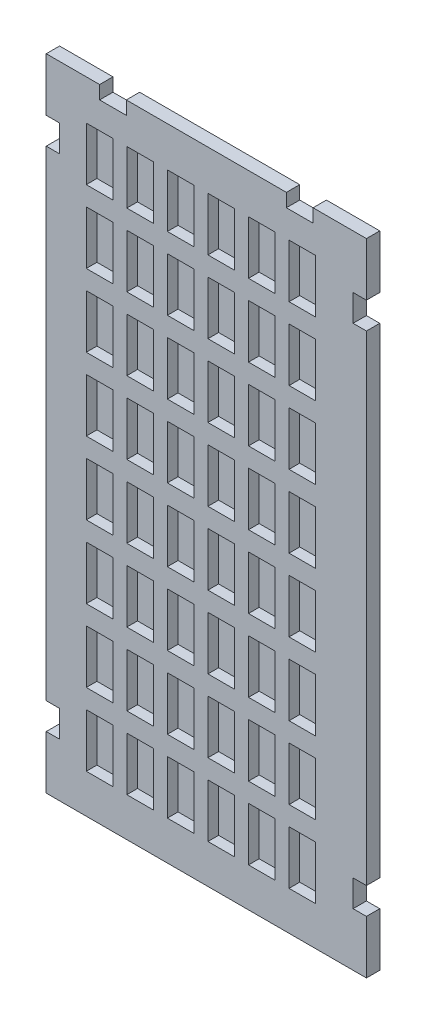
SolidWorks part; units mm, degrees
ref_plane "Front Plane" through (0, 0, 0) normal (0, 0, 1) x (1, 0, 0)
ref_plane "Top Plane" through (0, 0, 0) normal (0, 1, 0) x (1, 0, 0)
ref_plane "Right Plane" through (0, 0, 0) normal (1, 0, 0) x (0, 0, -1)
sketch "Sketch1" plane through (0, 0, 0) normal (0, 0, 1) x (1, 0, 0)
  line L0 (12.7, -152.4) -> (63.5, -152.4)
  line L1 (0, 0) -> (76.2, 0)
  line L2 (0, 0) -> (0, -152.4)
  line L3 (0, -152.4) -> (12.7, -152.4)
  line L4 (76.2, 0) -> (76.2, -152.4)
  line L5 (12.7, 0) -> (19.05, 0)
  line L6 (12.7, 0) -> (12.7, -3.175)
  line L7 (12.7, -3.175) -> (19.05, -3.175)
  line L8 (19.05, 0) -> (19.05, -3.175)
  line L9 (57.15, 0) -> (63.5, 0)
  line L10 (57.15, 0) -> (57.15, -3.175)
  line L11 (57.15, -3.175) -> (63.5, -3.175)
  line L12 (63.5, 0) -> (63.5, -3.175)
  line L13 (76.2, -12.7) -> (73.025, -12.7)
  line L14 (76.2, -12.7) -> (76.2, -19.05)
  line L15 (76.2, -19.05) -> (73.025, -19.05)
  line L16 (73.025, -12.7) -> (73.025, -19.05)
  line L17 (76.2, -133.35) -> (73.025, -133.35)
  line L18 (76.2, -133.35) -> (76.2, -139.7)
  line L19 (76.2, -139.7) -> (73.025, -139.7)
  line L20 (73.025, -133.35) -> (73.025, -139.7)
  line L25 (63.5, -152.4) -> (76.2, -152.4)
  line L29 (0, -139.7) -> (3.175, -139.7)
  line L30 (0, -139.7) -> (0, -133.35)
  line L31 (0, -133.35) -> (3.175, -133.35)
  line L32 (3.175, -139.7) -> (3.175, -133.35)
  line L33 (0, -19.05) -> (3.175, -19.05)
  line L34 (0, -19.05) -> (0, -12.7)
  line L35 (0, -12.7) -> (3.175, -12.7)
  line L36 (3.175, -19.05) -> (3.175, -12.7)
  dimension "D1" = 76.2
  dimension "D2" = 152.4
  dimension "D3" = 12.7
  dimension "D4" = 6.35
  dimension "D5" = 3.175
  dimension "D6" = 6.35
  dimension "D7" = 3.175
  dimension "D8" = 12.7
  dimension "D9" = 12.7
  dimension "D10" = 6.35
  dimension "D11" = 3.175
  dimension "D12" = 3.175
  dimension "D13" = 6.35
  dimension "D14" = 12.7
  dimension "D21" = 3.175
  dimension "D22" = 6.35
  dimension "D23" = 12.7
  dimension "D24" = 12.7
  dimension "D25" = 6.35
  dimension "D26" = 3.175
extrude "Boss-Extrude1" add sketch "Sketch1" along normal blind 3.175
sketch "Sketch2" plane through (0, 0, 3.175) normal (0, 0, 1) x (1, 0, 0)
  line L0 (12.7, -3.175) -> (19.05, -3.175) construction
  line L1 (9.525, -9.525) -> (15.875, -9.525)
  line L2 (9.525, -9.525) -> (9.525, -22.225)
  line L3 (9.525, -22.225) -> (15.875, -22.225)
  line L4 (15.875, -9.525) -> (15.875, -22.225)
  line L5 (9.525, -9.525) -> (15.875, -22.225) construction
  line L6 (9.525, -22.225) -> (15.875, -9.525) construction
  line L7 (3.175, -19.05) -> (3.175, -12.7) construction
  point P0 (12.7, -15.875)
  dimension "D1" = 6.35
  dimension "D2" = 6.35
  dimension "D3" = 12.7
  dimension "D4" = 6.35
extrude "Cut-Extrude1" cut sketch "Sketch2" against normal blind 2.54
pattern_linear "LPattern1" count 6 spacing 9.652 along (1, 0, 0) count 8 spacing 17.272 along (0, -1, 0) of "Cut-Extrude1"
